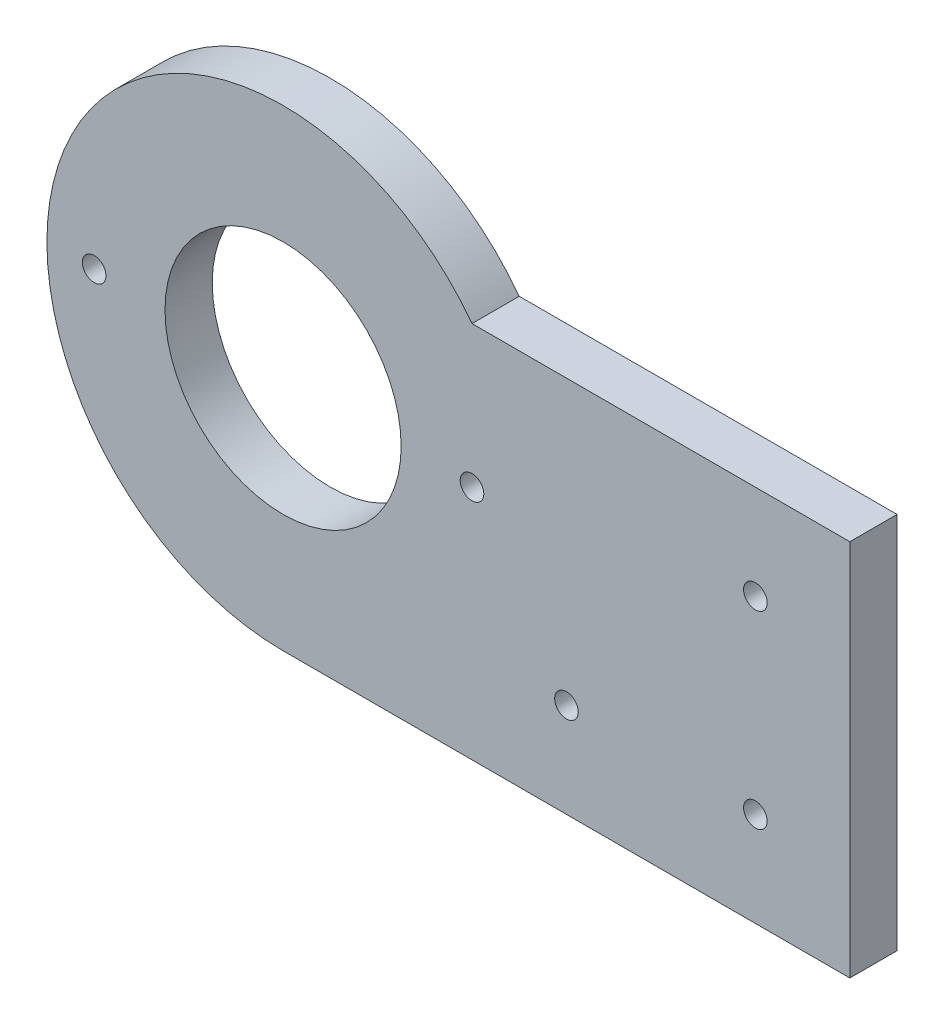
SolidWorks part; units mm, degrees
ref_plane "Front Plane" through (0, 0, 0) normal (0, 0, 1) x (1, 0, 0)
ref_plane "Top Plane" through (0, 0, 0) normal (0, 1, 0) x (1, 0, 0)
ref_plane "Right Plane" through (0, 0, 0) normal (1, 0, 0) x (0, 0, -1)
sketch "Sketch1" plane through (0, 0, 0) normal (0, 0, 1) x (1, 0, 0)
  line L0 (0, -31.75) -> (76.2, -31.75)
  line L1 (76.2, -31.75) -> (76.2, -6.35)
  line L2 (76.2, -6.35) -> (31.1085, -6.35)
  line L3 (25.4, 0) -> (-25.4, 0) construction
  line L4 (76.2, -19.05) -> (31.1085, -19.05) construction
  line L5 (31.1085, -19.05) -> (31.1085, -6.35) construction
  arc A0 (0, -31.75) -> (31.1085, -6.35) centre (0, 0) cw
  circle A1 centre (0, 0) radius 15.875
  circle A2 centre (-25.4, 0) radius 1.5875
  circle A3 centre (25.4, 0) radius 1.5875
  circle A4 centre (38.1, -19.05) radius 1.5875
  circle A5 centre (63.5, -19.05) radius 1.5875
  point P13 (0, 0)
  dimension "D1" = 31.75
  dimension "D4" = 31.75
  dimension "D5" = 3.175
  dimension "D7" = 3.175
  dimension "D2" = 25.4
  dimension "D3" = 76.2
  dimension "D6" = 50.8
  dimension "D8" = 12.7
  dimension "D9" = 25.4
extrude "Boss-Extrude1" add sketch "Sketch1" along normal blind 6.35
sketch "Sketch2" plane through (0, 0, 6.35) normal (0, 0, 1) x (1, 0, 0)
  line L0 (76.2, -6.35) -> (76.2, 19.05)
  line L1 (76.2, 19.05) -> (25.4, 19.05)
  line L4 (76.2, -6.35) -> (31.1085, -6.35) construction
  line L5 (31.1085, -6.35) -> (76.2, -6.35)
  line L6 (76.2, 6.35) -> (31.1085, 6.35) construction
  arc A0 (31.1085, -6.35) -> (0, -31.75) centre (0, 0) ccw construction
  arc A1 (25.4, 19.05) -> (31.1085, -6.35) centre (0, 0) cw
  circle A2 centre (63.5, 6.35) radius 1.5875
  circle A5 centre (63.5, -19.05) radius 1.5875 construction
  dimension "D1" = 25.4
  dimension "D2" = 12.7
extrude "Boss-Extrude2" add sketch "Sketch2" against normal up to surface (6.35 mm away) up to face at (39.6875, -19.05, 0)
